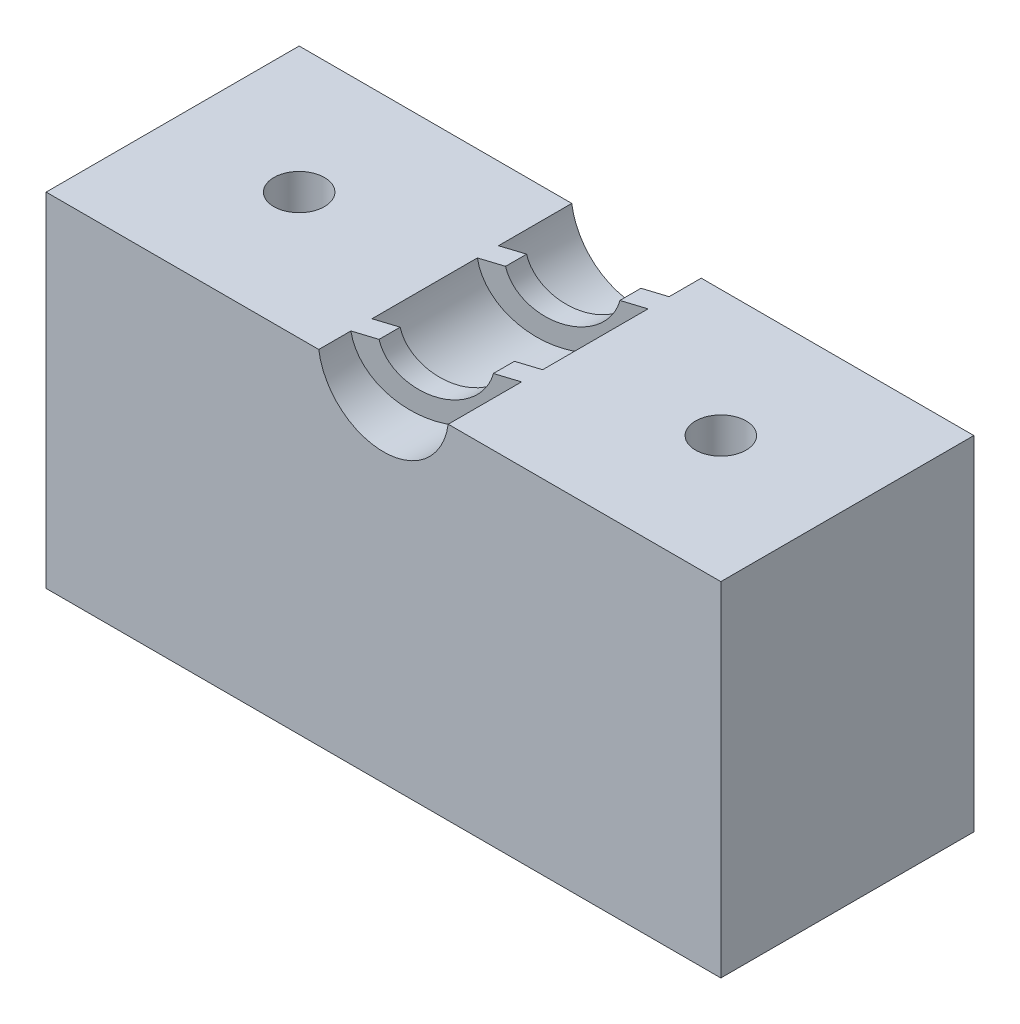
SolidWorks part; units mm, degrees
ref_plane "前视基准面" through (0, 0, 0) normal (0, 0, 1) x (1, 0, 0)
ref_plane "上视基准面" through (0, 0, 0) normal (0, 1, 0) x (1, 0, 0)
ref_plane "右视基准面" through (0, 0, 0) normal (1, 0, 0) x (0, 0, -1)
other "Configuration Table"
sketch "草图1" plane through (0, 0, 0) normal (0, 0, 1) x (1, 0, 0)
  line L1 (-8, -8) -> (8, -8)
  line L2 (-8, -8) -> (-8, 8)
  line L3 (-8, 8) -> (8, 8)
  line L4 (8, -8) -> (8, 8)
  line L5 (-8, -8) -> (8, 8) construction
  line L6 (-8, 8) -> (8, -8) construction
  circle A0 centre (0, 0) radius 1.55
  point P0 (0, 0)
  dimension "D3" = 3.1
  dimension "D1" = 16
  dimension "D2" = 16
extrude "凸台-拉伸1" add sketch "草图1" along normal mid plane 6
sketch "草图6" plane through (0, 0, 0) normal (0, 1, 0) x (1, 0, 0)
  line L0 (-1.55, -3) -> (1.55, -3) construction
  line L1 (1.55, 3) -> (-1.55, 3) construction
  line L2 (-1.55, -3) -> (1.55, -3)
  line L3 (1.55, 3) -> (-1.55, 3)
  line L4 (-1.55, 3) -> (-1.55, -3)
  line L5 (1.55, -3) -> (1.55, 3)
  line L6 (-1.55, 0.7565) -> (1.55, 1.7435)
  line L7 (1.55, 1.7435) -> (1.55, 2.2435)
  line L8 (1.55, 2.2435) -> (-1.55, 1.2565)
  line L9 (-1.55, -1.7435) -> (1.55, -0.7565)
  line L10 (-1.55, -2.2435) -> (1.55, -1.2565)
  line L11 (-2.0945, -0.6668) -> (3.135, 0.9981) construction
  line L12 (-3.1004, 0) -> (4.2723, 0) construction
  dimension "D1" = 2.5
  dimension "D2" = 0.5
  dimension "D3" = 0.5
  dimension "D4" = 17.66
extrude "凸台-拉伸2" add sketch "草图6" against normal up to surface (8 mm away) contours L4 L10 L5 L9 | L5 L8 L4 L6 up to face at (0, -8, 0)
sketch "草图7" plane through (0, 0, 0) normal (0, 0, 1) x (1, 0, 0)
  line L0 (0, 0) -> (-1.0279, -0.2141)
  line L1 (0, 0) -> (1.0279, -0.2141)
  line L2 (-1.0279, -0.2141) -> (-8, -0.2141)
  line L3 (1.0279, -0.2141) -> (8, -0.2141)
  line L6 (8, -8) -> (8, 8)
  line L7 (-8, -8) -> (8, -8)
  line L8 (-8, 8) -> (-8, -8)
  line L9 (8, 8) -> (-8, 8)
  line L10 (8, -8) -> (8, 8)
  line L11 (-8, -8) -> (8, -8)
  line L12 (-8, 8) -> (-8, -8)
  line L13 (8, 8) -> (-8, 8)
  circle A0 centre (0, 0) radius 1.05
  dimension "D1" = 2.1
  dimension "D2" = 0
  dimension "D3" = 156.47
extrude "切除-拉伸2" cut sketch "草图7" against normal through all both and the other way through all contours A0 L3 L10 L13 L12 L2 | L1 A0 L0 | L0 A0 L1
sketch "草图8" plane through (0, 0, 0) normal (0, 1, 0) x (1, 0, 0)
  line L0 (0, 5.5834) -> (0, -5.0797) construction
  circle A0 centre (-5, 0) radius 0.6
  circle A1 centre (5, 0) radius 0.6
  dimension "D2" = 1.2
  dimension "D3" = 10
extrude "切除-拉伸3" cut sketch "草图8" against normal through all
sketch "草图9" plane through (0, -8, 0) normal (0, -1, 0) x (1, 0, 0)
  line L4 (-8, -3) -> (8, -3)
  line L5 (8, -3) -> (8, 3)
  line L6 (8, 3) -> (-8, 3)
  line L7 (-8, 3) -> (-8, -3)
  line L8 (-8, -3) -> (8, -3)
  line L9 (8, -3) -> (8, 3)
  line L10 (8, 3) -> (-8, 3)
  line L11 (-8, 3) -> (-8, -3)
  circle A0 centre (-5, 0) radius 0.6 construction
  circle A1 centre (5, 0) radius 0.6 construction
  circle A2 centre (-5, 0) radius 0.6
  circle A3 centre (5, 0) radius 0.6
  dimension "D1" = 0
extrude "凸台-拉伸3" add sketch "草图9" along normal offset from surface (0.355 mm away) 0.6
equation "\"x\"=0.8094"
